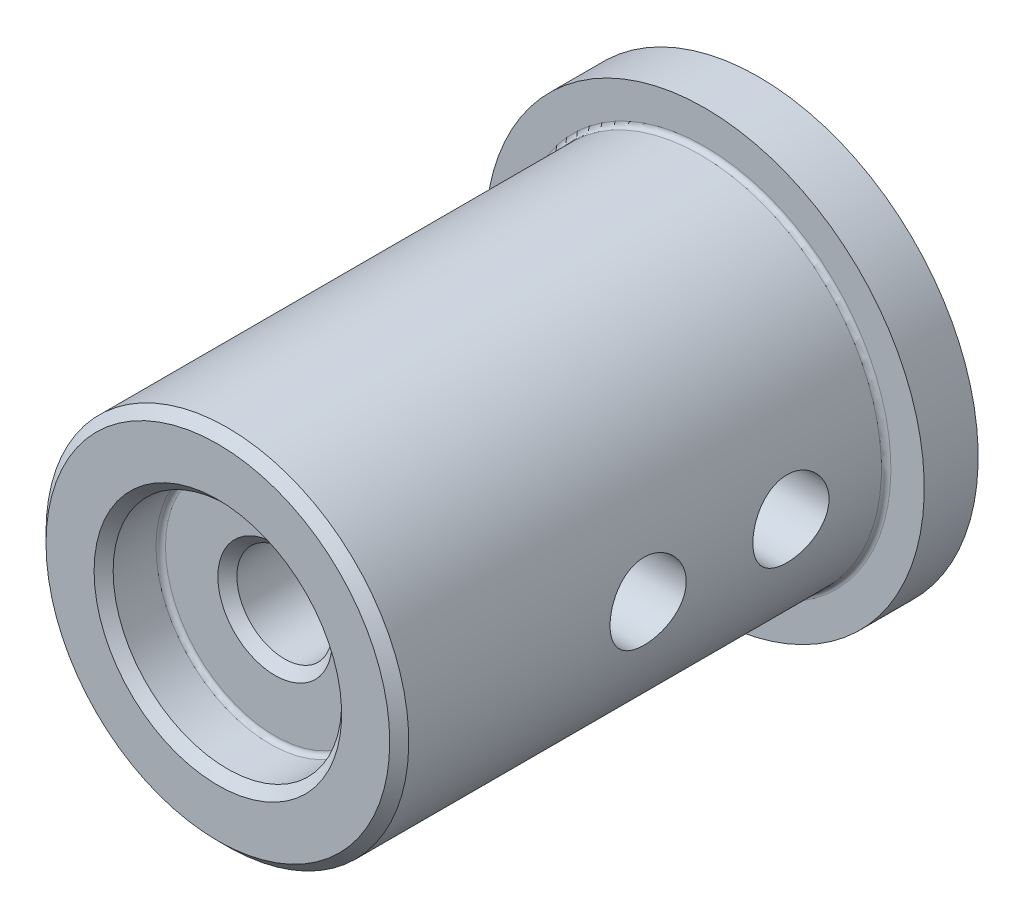
SolidWorks part; units mm, degrees
material "Alloy Steel"
ref_plane "Front Plane" through (0, 0, 0) normal (0, 0, 1) x (1, 0, 0)
ref_plane "Top Plane" through (0, 0, 0) normal (0, 1, 0) x (1, 0, 0)
ref_plane "Right Plane" through (0, 0, 0) normal (1, 0, 0) x (0, 0, -1)
sketch "Sketch1" plane through (0, 0, 0) normal (1, 0, 0) x (0, 0, -1)
  line L0 (-14.2, 0) -> (14.2, 0) construction
  line L1 (-14.2, 6) -> (-14.2, 9.525)
  line L2 (-14.2, 9.525) -> (14.2, 9.525)
  line L3 (14.2, 9.525) -> (14.2, 6)
  line L4 (14.2, 6) -> (-6.8, 6)
  line L5 (-6.8, 6) -> (-6.8, 2.5)
  line L6 (-6.8, 2.5) -> (-11.2, 2.5)
  line L7 (-11.2, 2.5) -> (-11.2, 6)
  line L8 (-11.2, 6) -> (-14.2, 6)
  dimension "D1" = 28.4
  dimension "D2" = 6
  dimension "D3" = 9.525
  dimension "D4" = 2.5
  dimension "D5" = 21
  dimension "D6" = 3
revolve "Revolve1" add sketch "Sketch1" angle 360 about L0
sketch "Sketch3" plane through (0, 0, 0) normal (1, 0, 0) x (0, 0, -1)
  line L0 (11.37, -17.6356) -> (11.37, 11.4271) construction
  line L1 (14.2, 9.525) -> (11.37, 9.525)
  line L2 (14.2, 9.525) -> (14.2, 11.525)
  line L3 (14.2, 11.525) -> (11.37, 11.525)
  line L4 (11.37, 9.525) -> (11.37, 11.525)
  line L5 (0, 0) -> (14.2, 0) construction
  line L6 (14.2, -9.525) -> (14.2, 9.525) construction
  dimension "D1" = 2
revolve "Revolve2" add sketch "Sketch3" angle 360 about L5
chamfer "Chamfer1" distance 0.5 angle 45 4 edges at (6, 0, -14.2) (9.525, 0, 14.2) (6, 0, 14.2) (2.5, 0, 11.2)
fillet "Fillet1" radius 0.25 2 edges at (6, 0, 11.2) (0, 9.525, -11.37)
sketch "Sketch2" plane through (0, 0, -14.2) normal (0, 0, -1) x (-1, 0, 0)
  line L1 (2, 7.1) -> (-2, 7.1)
  line L2 (2, 7.1) -> (2, 5.6569)
  line L3 (2, 5.6569) -> (-2, 5.6569)
  line L4 (-2, 7.1) -> (-2, 5.6569)
  line L5 (2, 7.1) -> (-2, 5.6569) construction
  line L6 (2, 5.6569) -> (-2, 7.1) construction
  circle A1 centre (0, 0) radius 6 construction
  point P0 (0, 6.3784)
  dimension "D1" = 7.1
  dimension "D2" = 4
extrude "Cut-Extrude1" [suppressed] cut sketch "Sketch2" against normal up to surface (21 mm away)
sketch "Sketch4" plane through (0, 0, 0) normal (1, 0, 0) x (0, 0, -1)
  line L0 (11.37, 11.525) -> (11.37, -11.525) construction
  circle A0 centre (6.37, 0) radius 2
  circle A1 centre (-1.13, 0) radius 2
  dimension "D3" = 4
  dimension "D1" = 12.5
  dimension "D2" = 5
extrude "Cut-Extrude2" cut sketch "Sketch4" along normal through all
sketch "Sketch5" plane through (0, 0, 0) normal (0, 1, 0) x (1, 0, 0)
  circle A0 centre (0, 0) radius 2
  dimension "D1" = 4
extrude "Cut-Extrude3" cut sketch "Sketch5" against normal through all
